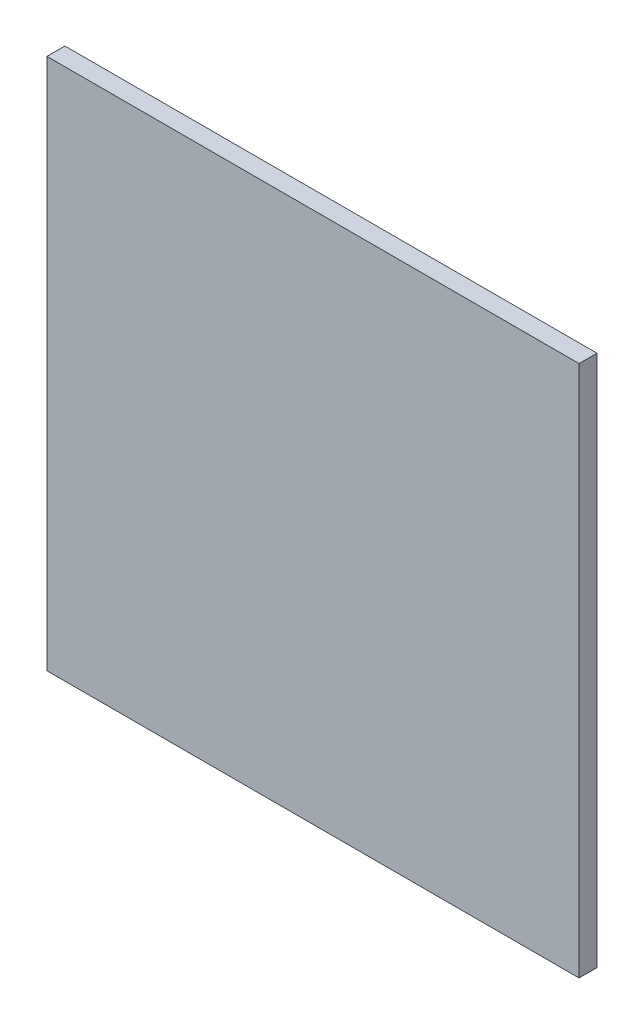
SolidWorks part; units mm, degrees
material "Acrílico (Impacto medio-alto)"
ref_plane "Alzado" through (0, 0, 0) normal (0, 0, 1) x (1, 0, 0)
ref_plane "Planta" through (0, 0, 0) normal (0, 1, 0) x (1, 0, 0)
ref_plane "Vista lateral" through (0, 0, 0) normal (1, 0, 0) x (0, 0, -1)
sketch "Croquis1" plane through (0, 0, 0) normal (0, 0, 1) x (1, 0, 0)
  line L1 (0, 82.7) -> (-80, 82.7)
  line L2 (0, 82.7) -> (0, 2.7)
  line L3 (0, 2.7) -> (-80, 2.7)
  line L4 (-80, 82.7) -> (-80, 2.7)
extrude "Saliente-Extruir1" add sketch "Croquis1" against normal blind 2.7
